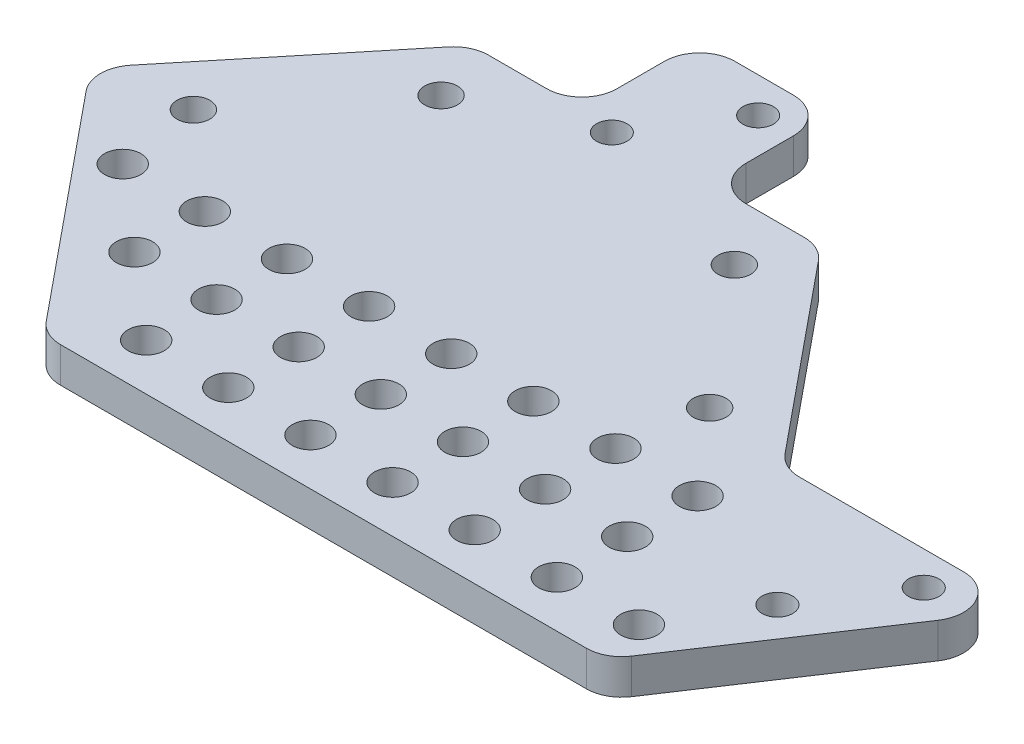
SolidWorks part; units mm, degrees
ref_plane "前视基准面" through (0, 0, 0) normal (0, 0, 1) x (1, 0, 0)
ref_plane "上视基准面" through (0, 0, 0) normal (0, 1, 0) x (1, 0, 0)
ref_plane "右视基准面" through (0, 0, 0) normal (1, 0, 0) x (0, 0, -1)
sketch "草图1" plane through (0, 0, 0) normal (0, 1, 0) x (1, 0, 0)
  line L0 (0, 0) -> (22, 0) construction
  line L1 (0, 0) -> (-22, 0) construction
  line L2 (0, 0) -> (0, 11.6082) construction
  line L3 (0, 11.6082) -> (-12.5, 11.6082) construction
  line L4 (-12.5, 11.6082) -> (-22, 0) construction
  line L5 (0, 11.6082) -> (12.5, 11.6082) construction
  line L6 (12.5, 11.6082) -> (22, 0) construction
  line L7 (0, 16.6082) -> (-14.869, 16.6082)
  line L8 (-14.869, 16.6082) -> (-32.5529, -5)
  line L9 (0, -5) -> (-32.5529, -5)
  line L10 (0, -5) -> (32.5529, -5)
  line L11 (14.869, 16.6082) -> (32.5529, -5)
  line L12 (0, 16.6082) -> (14.869, 16.6082)
  line L13 (-29.5129, -1.2854) -> (-26.4729, -5)
  line L14 (29.5129, -1.2854) -> (26.4729, -5)
  line L15 (0, 19.8997) -> (0, 11.6082)
  line L16 (29.5129, -1.2854) -> (50.5129, -1.2854)
  line L17 (-5.5, 26.6497) -> (5.5, 26.6497)
  line L18 (-5.5, 26.6497) -> (-5.5, 13.1497)
  line L19 (-12.081, -10.0248) -> (12.081, -10.0248) construction
  line L25 (-26.4729, -5) -> (-16.6522, -17)
  line L26 (-16.6522, -17) -> (16.6522, -17)
  line L27 (16.6522, -17) -> (26.4729, -5)
  line L28 (0, 0) -> (0, -19.0248)
  line L29 (-16.6522, -17) -> (-11.7419, -23)
  line L33 (-5.5, 13.1497) -> (5.5, 13.1497)
  line L36 (5.5, 26.6497) -> (5.5, 13.1497)
  line L39 (12.5, 11.6082) -> (0, 19.8997)
  line L40 (12.5, 11.6082) -> (41.9167, -7.9046)
  line L41 (-2.4875, 16.1497) -> (2.4875, 23.6497)
  line L42 (39.4292, -11.6546) -> (44.4041, -4.1546)
  line L43 (-5.5, 26.6497) -> (5.5, 13.1497) construction
  line L44 (-5.5, 13.1497) -> (5.5, 26.6497) construction
  line L45 (50.5129, -1.2854) -> (40.563, -16.2854)
  line L46 (21, -13.0248) -> (29.55, -13.0248)
  line L47 (16.6522, -17) -> (40.089, -17)
  line L48 (40.089, -17) -> (40.563, -16.2854)
  line L49 (-15.55, -13.0248) -> (21, -13.0248)
  line L50 (-11.7419, -23) -> (36.109, -23)
  line L51 (36.109, -23) -> (40.089, -17)
  line L52 (0, -16.0248) -> (0, -19.0248)
  line L53 (0, -16.0248) -> (5.8235, -16.0248) construction
  line L55 (40.3144, -19.0248) -> (-7, -19.0248)
  circle A0 centre (-12.5, 11.6082) radius 1.4
  circle A1 centre (12.5, 11.6082) radius 1.4
  circle A2 centre (-22, 0) radius 1.4
  circle A3 centre (22, 0) radius 1.4
  circle A8 centre (0, -13.0248) radius 1.55
  circle A9 centre (7, -13.0248) radius 1.55
  circle A10 centre (14, -13.0248) radius 1.55
  circle A11 centre (21, -13.0248) radius 1.55
  circle A13 centre (-14, -13.0248) radius 1.55
  circle A14 centre (-7, -13.0248) radius 1.55
  circle A15 centre (21, -7.0248) radius 1.55
  circle A16 centre (14, -7.0248) radius 1.55
  circle A17 centre (7, -7.0248) radius 1.55
  circle A18 centre (0, -7.0248) radius 1.55
  circle A19 centre (-7, -7.0248) radius 1.55
  circle A20 centre (-14, -7.0248) radius 1.55
  circle A21 centre (-21, -7.0248) radius 1.55
  circle A26 centre (-2.4875, 16.1497) radius 1.3
  circle A27 centre (2.4875, 23.6497) radius 1.3
  circle A28 centre (44.4041, -4.1546) radius 1.3
  circle A29 centre (39.4292, -11.6546) radius 1.3
  circle A30 centre (28, -13.0248) radius 1.55
  circle A32 centre (28, -7.0248) radius 1.55
  circle A33 centre (-7, -19.0248) radius 1.55
  circle A34 centre (0, -19.0248) radius 1.55
  circle A35 centre (7, -19.0248) radius 1.55
  circle A36 centre (14, -19.0248) radius 1.55
  circle A37 centre (21, -19.0248) radius 1.55
  circle A38 centre (28, -19.0248) radius 1.55
  circle A39 centre (35, -19.0248) radius 1.55
  point P26 (-22.8, 11.6082)
  point P28 (27.5, 11.6082)
  point P45 (0, -13.0248)
  point P62 (0, -10.0248)
  point P83 (0, 19.8997)
  point P86 (41.9167, -7.9046)
  dimension "D6" = 2.8
  dimension "D7" = 2.8
  dimension "D8" = 2.8
  dimension "D9" = 2.8
  dimension "D18" = 6
  dimension "D19" = 7
  dimension "D20" = 3
  dimension "D21" = 7
  dimension "D26" = 3.1
  dimension "D27" = 3.1
  dimension "D28" = 3.1
  dimension "2.9" = 3.1
  dimension "D29" = 3.1
  dimension "D22" = 7
  dimension "D23" = 7
  dimension "D24" = 2.6
  dimension "D33" = 2.6
  dimension "D34" = 2.6
  dimension "D35" = 2.6
  dimension "D16" = 3.1
  dimension "D43" = 3.1
  dimension "D44" = 3.1
  dimension "D45" = 3.1
  dimension "D46" = 3.1
  dimension "D47" = 3.1
  dimension "D48" = 3.1
  dimension "D49" = 3.1
  dimension "D1" = 12.5
  dimension "D2" = 22
  dimension "D3" = 22
  dimension "D4" = 15
  dimension "D5" = 12.5
  dimension "D11" = 4.8
  dimension "D12" = 4.8
  dimension "D13" = 11
  dimension "D14" = 13.5
  dimension "D15" = 21
  dimension "D17" = 3
  dimension "D25" = 12
  dimension "D30" = 7
  dimension "D31" = 7
  dimension "D32" = 7
  dimension "D36" = 9
  dimension "D37" = 9
  dimension "D38" = 50.3
  dimension "D39" = 35.3
  dimension "D40" = 7
  dimension "D41" = 7
  dimension "D42" = 7
  dimension "D50" = 6
  dimension "D10" = 5
extrude "凸台-拉伸1" add sketch "草图1" along normal blind 3
fillet "圆角6" radius 3 2 edges at (5.5, 1.5, -16.6082) (-5.5, 1.5, -16.6082)
fillet "圆角7" radius 3 9 edges at (14.869, 1.5, -16.6082) (29.5129, 1.5, 1.2854) (50.5129, 1.5, 1.2854) (36.109, 1.5, 23) (-11.7419, 1.5, 23) (-29.5129, 1.5, 1.2854) (-14.869, 1.5, -16.6082) (5.5, 1.5, -26.6497) (-5.5, 1.5, -26.6497)
